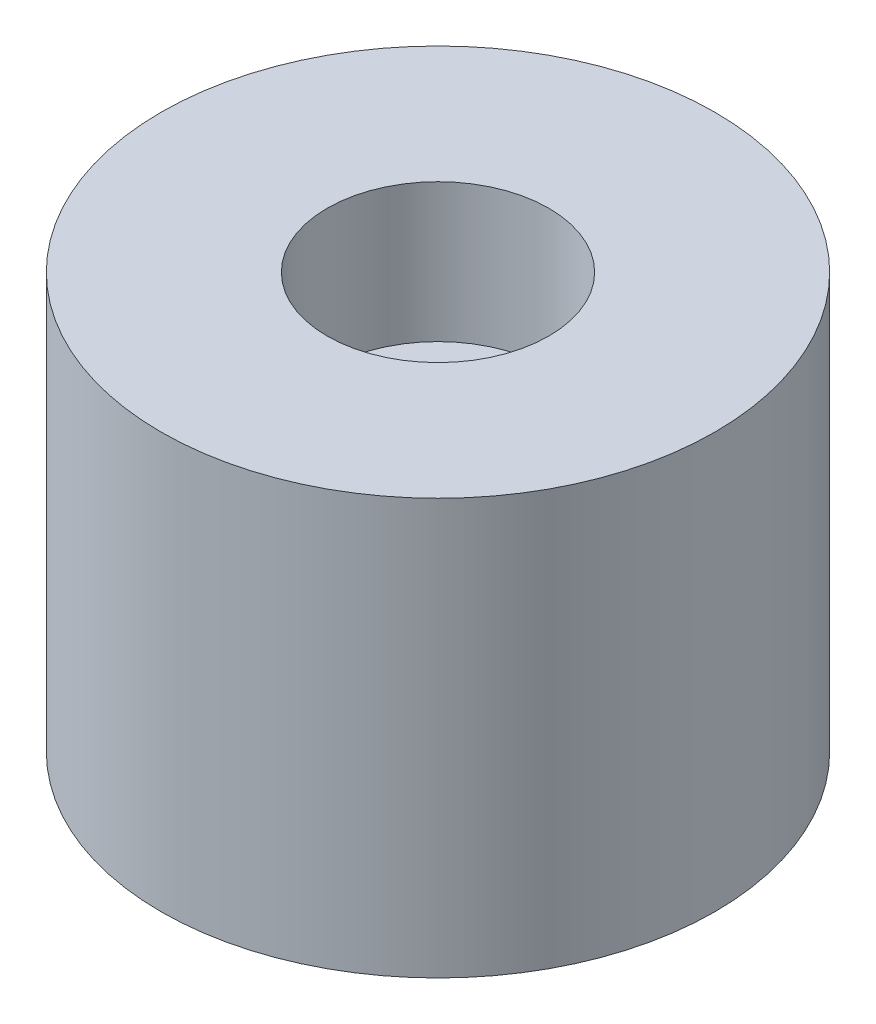
SolidWorks part; units mm, degrees
ref_plane "Front Plane" through (0, 0, 0) normal (0, 0, 1) x (1, 0, 0)
ref_plane "Top Plane" through (0, 0, 0) normal (0, 1, 0) x (1, 0, 0)
ref_plane "Right Plane" through (0, 0, 0) normal (1, 0, 0) x (0, 0, -1)
sketch "Sketch1" plane through (0, 0, 0) normal (0, 1, 0) x (1, 0, 0)
  circle A0 centre (0, 0) radius 10
  dimension "D1" = 20
extrude "Boss-Extrude1" add sketch "Sketch1" along normal blind 15
sketch "Sketch2" plane through (0, 15, 0) normal (0, 1, 0) x (1, 0, 0)
  circle A0 centre (0, 0) radius 4
  dimension "D1" = 8
extrude "Cut-Extrude1" cut sketch "Sketch2" against normal blind 5
